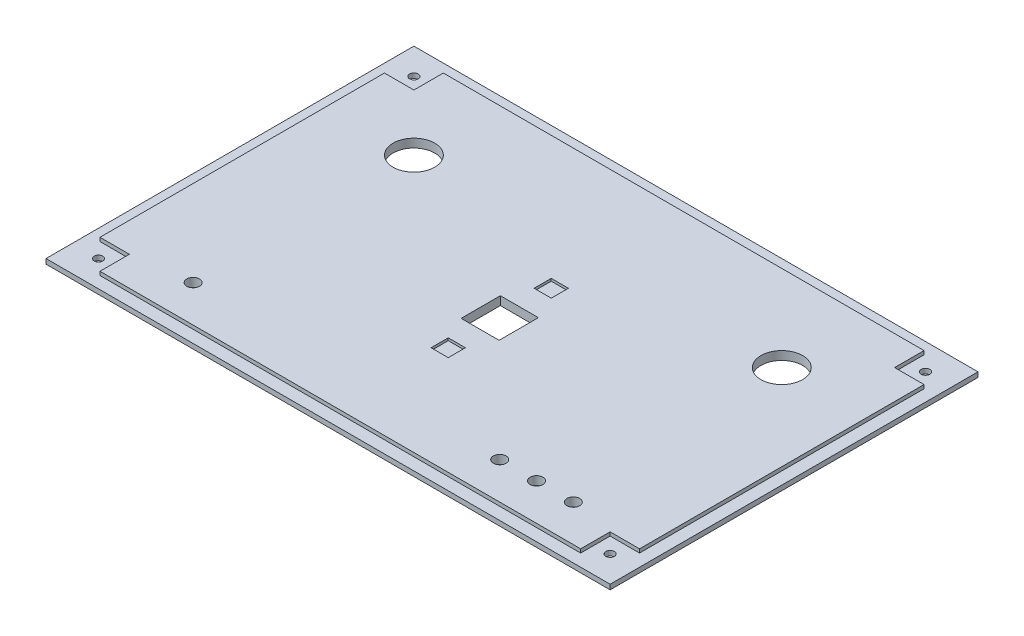
SolidWorks part; units mm, degrees
ref_plane "Front Plane" through (0, 0, 0) normal (0, 0, 1) x (1, 0, 0)
ref_plane "Top Plane" through (0, 0, 0) normal (0, 1, 0) x (1, 0, 0)
ref_plane "Right Plane" through (0, 0, 0) normal (1, 0, 0) x (0, 0, -1)
sketch "Sketch1" plane through (0, 0, 0) normal (0, 1, 0) x (1, 0, 0)
  line L0 (0, 92.7616) -> (0, -104.3795) construction
  line L1 (-173.3608, 0) -> (180.2589, 0) construction
  line L2 (-110, 70) -> (110, 70)
  line L3 (-115, -75) -> (115, -75)
  line L4 (-115, -75) -> (-115, 75)
  line L5 (-115, 75) -> (115, 75)
  line L6 (115, -75) -> (115, 75)
  line L7 (-115, -75) -> (115, 75) construction
  line L8 (-115, 75) -> (115, -75) construction
  line L9 (110, -70) -> (110, 70)
  line L10 (-110, -70) -> (110, -70)
  line L11 (-110, -70) -> (-110, 70)
  point P5 (0, 0)
  dimension "D1" = 5
  dimension "D2" = 230
  dimension "D3" = 150
extrude "Boss-Extrude1" add sketch "Sketch1" along normal blind 3.5 contours L4 L3 L6 L5
sketch "Sketch2" plane through (0, 3.5, 0) normal (0, 1, 0) x (1, 0, 0)
  line L8 (110, 70) -> (-110, 70)
  line L9 (-110, 70) -> (-110, -70)
  line L10 (-110, -70) -> (110, -70)
  line L11 (110, -70) -> (110, 70)
  line L12 (110, 70) -> (-110, 70)
  line L13 (-110, 70) -> (-110, -70)
  line L14 (-110, -70) -> (110, -70)
  line L15 (110, -70) -> (110, 70)
  line M5 (115, 75) -> (-115, 75)
  line M6 (-115, 75) -> (-115, -75)
  line M7 (-115, -75) -> (115, -75)
  line M8 (115, -75) -> (115, 75)
  dimension "D1" = 5
sketch "Sketch4" plane through (0, 0, 0) normal (0, -1, 0) x (1, 0, 0)
  line L0 (0, 85.9323) -> (0, -93.7204) construction
  line L1 (-141.298, 0) -> (140.9659, 0) construction
  line L2 (-115, -35) -> (119.381, -35) construction
  line L3 (-115, 75) -> (-115, -75) construction
  line L4 (-133.6335, 5) -> (181.3904, 5) construction
  line L5 (-115, -75) -> (115, -75) construction
  line L6 (-7.75, 13) -> (-7.75, -3)
  line L7 (-7.75, 13) -> (7.75, 13)
  line L8 (-7.75, -3) -> (7.75, -3)
  line L9 (7.75, 13) -> (7.75, -3)
  line L10 (-7.75, 13) -> (7.75, -3) construction
  line L11 (-7.75, -3) -> (7.75, 13) construction
  line L12 (-115, -75) -> (115, -75) construction
  circle A1 centre (-75, -35) radius 8.5
  circle A2 centre (75, -35) radius 8.5
  point P5 (0, 5)
  dimension "D1" = 40
  dimension "D4" = 16
  dimension "D5" = 17
  dimension "D2" = 15.5
  dimension "D3" = 40
  dimension "D6" = 80
extrude "Cut-Extrude2" cut sketch "Sketch4" against normal blind 100
extrude "Cut-Extrude3" cut sketch "Sketch2" against normal blind 1.5 contours L15 L14 L13 L12 M8 M5 M6 M7
sketch "Sketch5" plane through (0, 3.5, 0) normal (0, 1, 0) x (1, 0, 0)
  line L0 (-104.3, 70) -> (-104.3, 58.3) construction
  line L1 (-110, 70) -> (-98, 70)
  line L2 (-110, 70) -> (-110, 58)
  line L3 (-110, 58) -> (-98, 58)
  line L4 (-98, 70) -> (-98, 58)
  line L5 (-110, 64.3) -> (-98.3, 64.3) construction
  line L7 (115, 75) -> (-115, 75) construction
  line L8 (-115, 75) -> (-115, -75) construction
  circle A0 centre (-104.3, 64.3) radius 1.75
  point P11 (0, 0)
  point P12 (0, 0)
  point P17 (0, 0)
  line M10 (110, 70) -> (-110, 70)
  line M11 (-110, 70) -> (-110, -70)
  dimension "D3" = 3.5
  dimension "D1" = 12
  dimension "D2" = 12
  dimension "D4" = 10.7
  dimension "D5" = 10.7
extrude "Cut-Extrude4" cut sketch "Sketch5" against normal up to surface (1.5 mm away) contours L4 L3 A0 M10 M11 up to face at (0, 2, 0)
sketch "Sketch7" plane through (0, 3.5, 0) normal (0, 1, 0) x (1, 0, 0)
  line L0 (-115, 75) -> (-115, -75) construction
  line L1 (115, 75) -> (-115, 75) construction
  circle A0 centre (-104.3, 64.3) radius 1.75
  circle M2 centre (-104.3, 64.3) radius 1.75
  dimension "D1" = 3.5
  dimension "D2" = 10.7
  dimension "D3" = 10.7
extrude "Cut-Extrude5" cut sketch "Sketch7" against normal blind 10 contours A0 M2
mirror "Mirror1" about plane through (0, 0, 0) normal (1, 0, 0) of "Cut-Extrude5", "Cut-Extrude4"
mirror "Mirror2" about plane through (0, 0, 0) normal (0, 0, 1) of "Cut-Extrude5", "Mirror1", "Cut-Extrude4"
sketch "Sketch8" plane through (0, 0, 0) normal (0, -1, 0) x (1, 0, 0)
  line L0 (-98.1906, 55) -> (98.5649, 55) construction
  line L1 (-115, 75) -> (115, 75) construction
  line L2 (115, 75) -> (115, -75) construction
  line L3 (-115, 75) -> (-115, -75) construction
  circle A0 centre (50, 55) radius 2.6
  circle A1 centre (65, 55) radius 2.6
  circle A2 centre (80, 55) radius 2.6
  circle A3 centre (-75, 55) radius 2.6
  dimension "D2" = 5.2
  dimension "D3" = 5.2
  dimension "D4" = 5.2
  dimension "D5" = 5.2
  dimension "D1" = 20
  dimension "D6" = 65
  dimension "D7" = 15
  dimension "D8" = 15
  dimension "D9" = 40
extrude "Cut-Extrude6" cut sketch "Sketch8" against normal blind 10 contours A3 L0 | L0 A3 | A0 | A1 | A2
sketch "Sketch9" plane through (0, 3.5, 0) normal (0, 1, 0) x (1, 0, 0)
  line L0 (-7.75, 3) -> (7.75, -13) construction
  line L1 (-7.75, -13) -> (7.75, 3) construction
  line L2 (0, -5) -> (-77.9104, -5) construction
  line L3 (-53.6502, 12.5) -> (45.5962, 12.5) construction
  line L4 (-46.2067, -22.5) -> (57.175, -22.5) construction
  line L5 (20.7846, 12.5) -> (20.7846, -22.5) construction
  line L6 (0, 39.2297) -> (0, -59.7411) construction
  line L8 (-3.5, 19.5) -> (3.5, 19.5)
  line L9 (-3.5, 19.5) -> (-3.5, 12.5)
  line L10 (-3.5, 12.5) -> (3.5, 12.5)
  line L11 (3.5, 19.5) -> (3.5, 12.5)
  line L12 (-3.5, 19.5) -> (3.5, 12.5) construction
  line L13 (-3.5, 12.5) -> (3.5, 19.5) construction
  line L14 (-3.5, -29.5) -> (3.5, -29.5)
  line L15 (-3.5, -29.5) -> (-3.5, -22.5)
  line L16 (-3.5, -22.5) -> (3.5, -22.5)
  line L17 (3.5, -29.5) -> (3.5, -22.5)
  line L18 (-3.5, -29.5) -> (3.5, -22.5) construction
  line L19 (-3.5, -22.5) -> (3.5, -29.5) construction
  point P16 (20.7846, -5)
  point P20 (0, 16)
  point P25 (0, -26)
  dimension "D1" = 35
  dimension "D2" = 7
  dimension "D3" = 7
  dimension "D4" = 7
  dimension "D5" = 7
extrude "Cut-Extrude7" cut sketch "Sketch9" against normal blind 1
